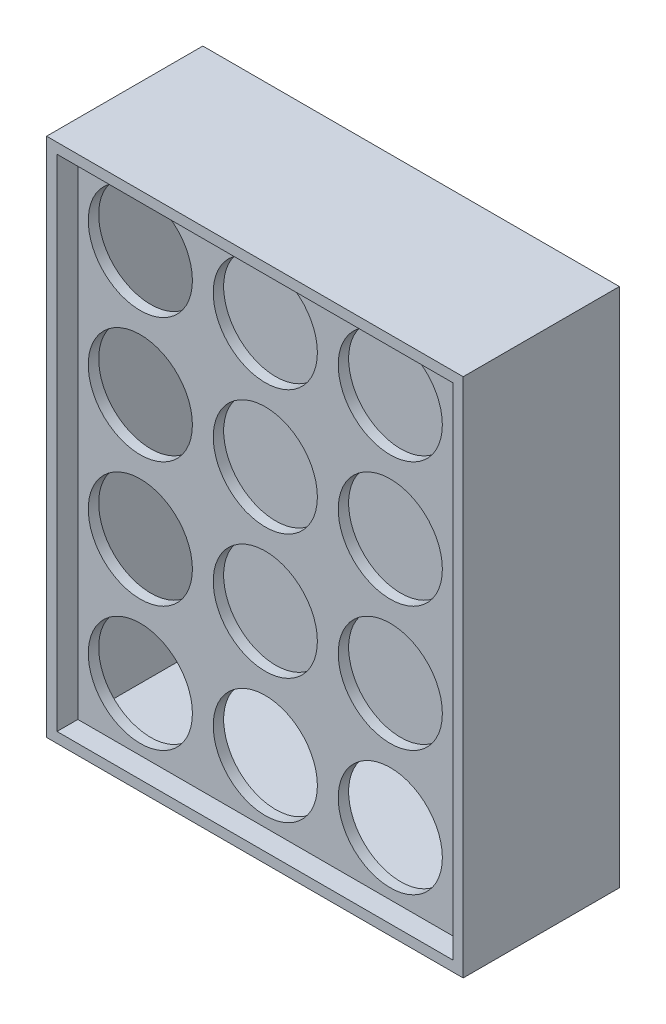
SolidWorks part; units mm, degrees
ref_plane "Front Plane" through (0, 0, 0) normal (0, 0, 1) x (1, 0, 0)
ref_plane "Top Plane" through (0, 0, 0) normal (0, 1, 0) x (1, 0, 0)
ref_plane "Right Plane" through (0, 0, 0) normal (1, 0, 0) x (0, 0, -1)
sketch "Sketch1" plane through (0, 0, 0) normal (0, 0, 1) x (1, 0, 0)
  line L1 (0, 0) -> (200, 0)
  line L2 (0, 0) -> (0, -250)
  line L3 (0, -250) -> (200, -250)
  line L4 (200, 0) -> (200, -250)
  dimension "D1" = 200
  dimension "D2" = 250
extrude "Boss-Extrude1" add sketch "Sketch1" along normal blind 5
sketch "Sketch2" plane through (0, 0, 5) normal (0, 0, 1) x (1, 0, 0)
  line L0 (5, -5) -> (5, -245)
  line L1 (0, 0) -> (200, 0)
  line L2 (0, 0) -> (0, -250)
  line L3 (0, -250) -> (200, -250)
  line L4 (200, 0) -> (200, -250)
  line L5 (5, -245) -> (195, -245)
  line L6 (195, -5) -> (195, -245)
  line L7 (5, -5) -> (195, -5)
  dimension "D1" = 5
extrude "Boss-Extrude2" add sketch "Sketch2" along normal blind 70
sketch "Sketch3" plane through (0, 0, 75) normal (0, 0, 1) x (1, 0, 0)
  line L1 (5, -5) -> (195, -5)
  line L2 (5, -5) -> (5, -245)
  line L3 (5, -245) -> (195, -245)
  line L4 (195, -5) -> (195, -245)
extrude "Boss-Extrude3" add sketch "Sketch3" along normal blind 5 from offset 15 offset against normal yes
sketch "Sketch4" plane through (0, 0, 65) normal (0, 0, 1) x (1, 0, 0)
  line L0 (5, -5) -> (5, -245) construction
  line L1 (195, -5) -> (5, -5) construction
  circle A0 centre (35, -35) radius 25
  circle A12 centre (95, -35) radius 25
  circle A13 centre (155, -35) radius 25
  circle A14 centre (95, -95) radius 25
  circle A15 centre (155, -95) radius 25
  circle A16 centre (95, -155) radius 25
  circle A17 centre (155, -155) radius 25
  circle A18 centre (95, -215) radius 25
  circle A19 centre (155, -215) radius 25
  circle A20 centre (35, -95) radius 25
  circle A21 centre (35, -155) radius 25
  circle A22 centre (35, -215) radius 25
  dimension "D1" = 50
  dimension "D2" = 30
  dimension "D3" = 30
  dimension "D4" = 3
  dimension "D5" = 4
extrude "Cut-Extrude1" cut sketch "Sketch4" against normal blind 5
